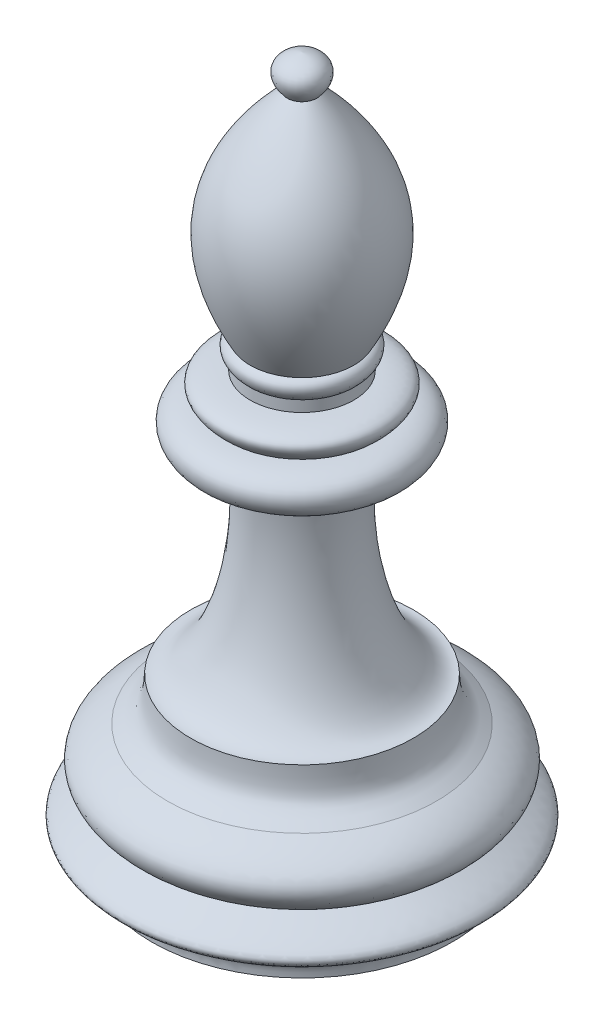
SolidWorks part; units mm, degrees
ref_plane "Front Plane" through (0, 0, 0) normal (0, 0, 1) x (1, 0, 0)
ref_plane "Top Plane" through (0, 0, 0) normal (0, 1, 0) x (1, 0, 0)
ref_plane "Right Plane" through (0, 0, 0) normal (1, 0, 0) x (0, 0, -1)
sketch "Sketch1" plane through (0, 0, 0) normal (0, 0, 1) x (1, 0, 0)
  line L0 (0, -39.3057) -> (0, 677.1059) construction
  line L1 (0, 0) -> (141.0484, 0)
  line L2 (0, 0) -> (0, 652.4166)
  line L4 (48.6949, 394.1286) -> (48.6949, 404.4745)
  spline S0 degree 3 poles (141.0484, 0) (140.9491, 13.5279) (142.5401, 11.5197) (158.207, 21.7716) knots 0 0 0 0 1 1 1 1
  spline S1 degree 2 poles (139.1426, 54.2717) (181.6095, 83.2322) (126.2192, 107.0462) knots 0 0 0 1 1 1
  spline S2 degree 3 poles (126.2192, 107.0462) (109.0403, 118.2002) (105.6669, 117.2796) (104.4538, 147.2817) knots 0 0 0 0 1 1 1 1
  spline S3 degree 3 poles (104.4538, 147.2817) (67.8132, 144.5741) (36.8704, 252.8788) (51.6157, 334.1463) knots 0 0 0 0 1 1 1 1
  spline S4 degree 3 poles (51.6157, 334.1463) (67.6045, 334.581) (79.4631, 334.8096) (98.8383, 340.6789) (105.1894, 369.5959) (68.7966, 370.3165) knots 0 0 0 0 0.25153 0.35153 1 1 1 1
  spline S5 degree 3 poles (68.7966, 370.3165) (83.6407, 383.4201) (82.4851, 393.3712) (48.6949, 394.1286) knots 0 0 0 0 1 1 1 1
  spline S6 degree 3 poles (48.6949, 404.4745) (56.0929, 410.8384) (56.5193, 419.3432) (48.6949, 422.4528) knots 0 0 0 0 1 1 1 1
  spline S7 degree 3 poles (48.6949, 422.4528) (94.8727, 505.4931) (73.8444, 562.2747) (13.8038, 621.9416) knots 0 0 0 0 1 1 1 1
  spline S8 degree 3 poles (13.8038, 621.9416) (27.2026, 636.6938) (20.6379, 649.2413) (0, 652.4166) knots 0 0 0 0 1 1 1 1
  spline S9 degree 3 poles (158.207, 21.7716) (180.3161, 34.0068) (168.8699, 38.0231) (139.1426, 54.2717) knots 0 0 0 0 1 1 1 1
revolve "Revolve1" add sketch "Sketch1" angle 360 about L0
scale "Scale1" scale about origin uniform scaling yes scale factor 0.5
